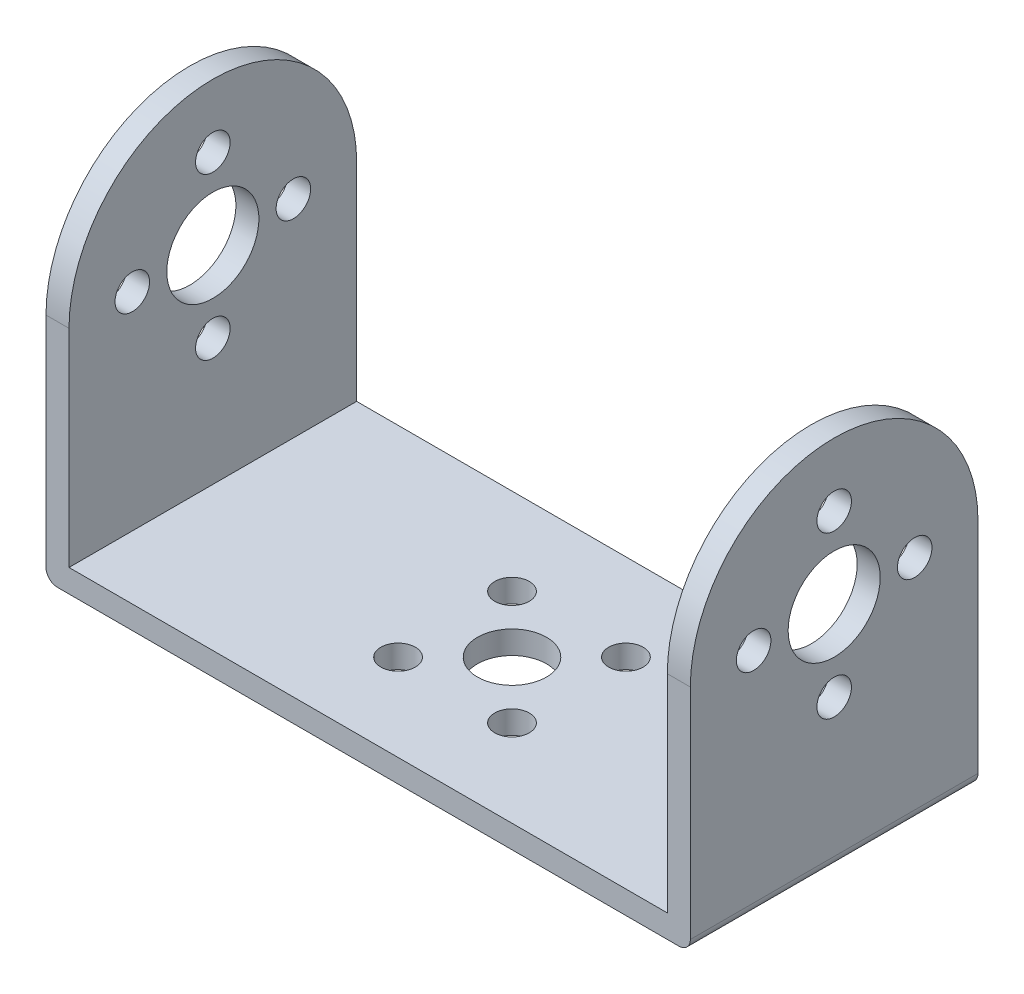
SolidWorks part; units mm, degrees
ref_plane "前视基准面" through (0, 0, 0) normal (0, 0, 1) x (1, 0, 0)
ref_plane "上视基准面" through (0, 0, 0) normal (0, 1, 0) x (1, 0, 0)
ref_plane "右视基准面" through (0, 0, 0) normal (1, 0, 0) x (0, 0, -1)
sketch "草图1" plane through (0, 0, 0) normal (0, 1, 0) x (1, 0, 0)
  line L1 (-20.3457, 13.2314) -> (35.6543, 13.2314)
  line L2 (-20.3457, 13.2314) -> (-20.3457, -11.7686)
  line L3 (-20.3457, -11.7686) -> (35.6543, -11.7686)
  line L4 (35.6543, 13.2314) -> (35.6543, -11.7686)
  dimension "D1" = 25
  dimension "D2" = 56
extrude "凸台-拉伸1" add sketch "草图1" along normal blind 2
sketch "草图2" plane through (0, 2, 0) normal (0, 1, 0) x (1, 0, 0)
  line L0 (7.6543, 13.2314) -> (7.6543, -11.7686) construction
  line L1 (35.6543, 13.2314) -> (-20.3457, 13.2314) construction
  line L2 (-20.3457, -11.7686) -> (35.6543, -11.7686) construction
  line L3 (-20.3457, 0.7314) -> (35.6543, 0.7314) construction
  line L4 (-20.3457, 13.2314) -> (-20.3457, -11.7686) construction
  line L5 (35.6543, -11.7686) -> (35.6543, 13.2314) construction
  circle A0 centre (7.6543, 0.7314) radius 3
  circle A1 centre (7.6543, 0.7314) radius 7 construction
  circle A3 centre (12.604, 5.6811) radius 1.5
  circle A4 centre (2.7045, 5.6811) radius 1.5
  circle A5 centre (12.604, -4.2184) radius 1.5
  circle A6 centre (2.7045, -4.2184) radius 1.5
  point P26 (7.6543, 0.7314)
extrude "切除-拉伸1" cut sketch "草图2" against normal through all
sketch "草图3" plane through (-20.3457, 0, 0) normal (-1, 0, 0) x (0, 0, 1)
  line L0 (-13.2314, 20) -> (-13.2314, 2)
  line L1 (11.7686, 20) -> (11.7686, 2)
  line L2 (-13.2314, 0) -> (11.7686, 0) construction
  line L5 (-13.2314, 2) -> (11.7686, 2)
  arc A0 (11.7686, 20) -> (-13.2314, 20) centre (-0.7314, 20) ccw
  dimension "D4" = 12.5
  dimension "D1" = 20
extrude "凸台-拉伸2" add sketch "草图3" against normal blind 2
sketch "草图4" plane through (-20.3457, 0, 0) normal (-1, 0, 0) x (0, 0, 1)
  line L0 (-13.2314, 20) -> (11.7686, 20) construction
  line L1 (-0.7314, 32) -> (-0.7314, 44.5) construction
  circle A1 centre (-0.7314, 20) radius 4
  circle A2 centre (-0.7314, 27) radius 1.5
  circle A3 centre (6.2686, 20) radius 1.5
  circle A4 centre (-0.7314, 13) radius 1.5
  circle A5 centre (-7.7314, 20) radius 1.5
  point P21 (-0.7314, 20)
  dimension "D1" = 7
  dimension "D2" = 4
extrude "切除-拉伸2" cut sketch "草图4" against normal up to next
ref_plane "基准面1" through (7.6543, 0, 0) normal (-1, 0, 0) x (0, 0, 1)
mirror "镜向1" about plane through (7.6543, 0, 0) normal (-1, 0, 0) of "切除-拉伸2", "凸台-拉伸2"
fillet "圆角1" radius 1 2 edges at (35.6543, 0, -0.7314) (-20.3457, 0, -0.7314)
